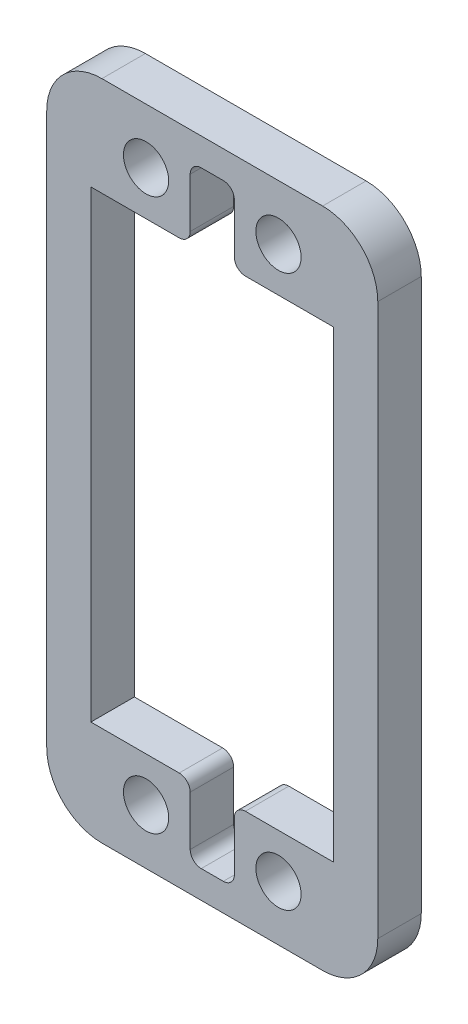
SolidWorks part; units mm, degrees
ref_plane "Alzado" through (0, 0, 0) normal (0, 0, 1) x (1, 0, 0)
ref_plane "Planta" through (0, 0, 0) normal (0, 1, 0) x (1, 0, 0)
ref_plane "Vista lateral" through (0, 0, 0) normal (1, 0, 0) x (0, 0, -1)
sketch "Croquis1" plane through (0, 0, 0) normal (0, 0, 1) x (1, 0, 0)
  line L0 (-15, 30) -> (15, 30)
  line L1 (15, 30) -> (15, -30)
  line L2 (15, -30) -> (-15, -30)
  line L3 (-15, -30) -> (-15, 30)
  line L4 (0, 0) -> (3.1755, 0) construction
  line L5 (0, 0) -> (0, 1.2752) construction
  dimension "D1" = 60
  dimension "D2" = 30
extrude "Saliente-Extruir1" add sketch "Croquis1" along normal blind 3.94
sketch "Croquis2" plane through (0, 0, 0) normal (0, 0, -1) x (-1, 0, 0)
  line L0 (-11, 21) -> (11, 21)
  line L1 (11, 21) -> (11, -21)
  line L2 (11, -21) -> (-11, -21)
  line L3 (-11, -21) -> (-11, 21)
  line L4 (0, 0) -> (17.9824, 0) construction
  line L5 (0, 0) -> (0, 11.2002) construction
  dimension "D1" = 22
  dimension "D2" = 42
extrude "Cortar-Extruir1" cut sketch "Croquis2" against normal through all
sketch "Croquis3" plane through (0, 0, 0) normal (0, 0, -1) x (-1, 0, 0)
  line L0 (0, 0) -> (-26.2125, 0) construction
  line L1 (0, 0) -> (0, 9.0898) construction
  line L2 (-2, 21) -> (-2, 27.5)
  line L3 (11, 21) -> (-11, 21) construction
  line L4 (-2, 27.5) -> (2, 27.5)
  line L5 (2, 27.5) -> (2, -27.5)
  line L6 (2, -27.5) -> (-2, -27.5)
  line L7 (-2, -27.5) -> (-2, 21)
  circle A0 centre (-6, 25) radius 2.05
  circle A1 centre (6, 25) radius 2.05
  circle A2 centre (-6, -25) radius 2.05
  circle A3 centre (6, -25) radius 2.05
  dimension "D1" = 4.1
  dimension "D2" = 4.1
  dimension "D3" = 4.1
  dimension "D4" = 4.1
  dimension "D5" = 12
  dimension "D6" = 12
  dimension "D7" = 50
  dimension "D8" = 25
  dimension "D9" = 4
  dimension "D10" = 55
extrude "Cortar-Extruir2" cut sketch "Croquis3" against normal through all
fillet "Redondeo1" radius 5 4 edges at (-15, -30, 1.97) (15, -30, 1.97) (15, 30, 1.97) (-15, 30, 1.97)
fillet "Redondeo3" radius 1 8 edges at (-2, -27.5, 1.97) (-2, -21, 1.97) (2, -21, 1.97) (2, -27.5, 1.97) (2, 27.5, 1.97) (-2, 27.5, 1.97) (2, 21, 1.97) (-2, 21, 1.97)
